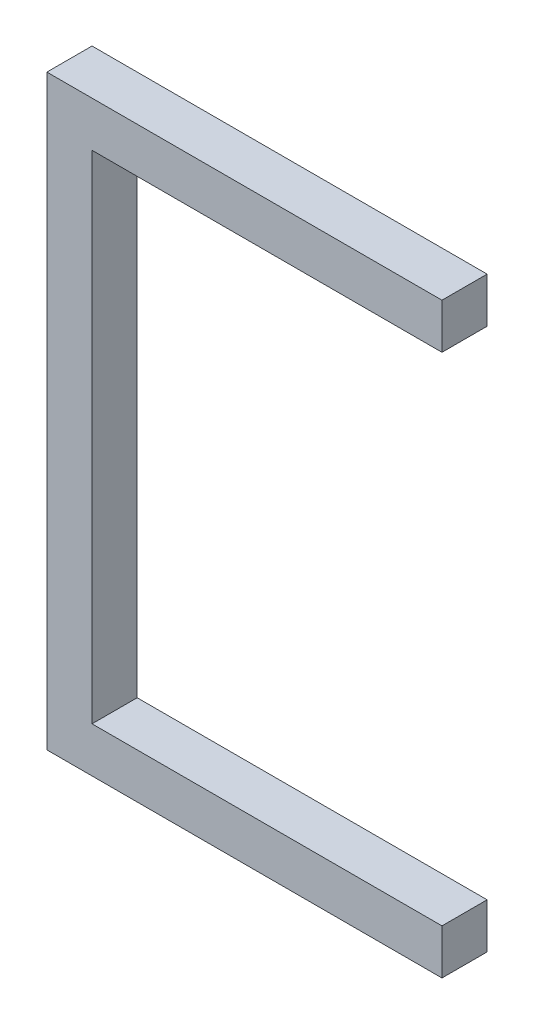
SolidWorks part; units mm, degrees
ref_plane "Front Plane" through (0, 0, 0) normal (0, 0, 1) x (1, 0, 0)
ref_plane "Top Plane" through (0, 0, 0) normal (0, 1, 0) x (1, 0, 0)
ref_plane "Right Plane" through (0, 0, 0) normal (1, 0, 0) x (0, 0, -1)
sketch "Sketch2" plane through (0, 0, 0) normal (0, 0, 1) x (1, 0, 0)
  line L14 (18.0516, 338.5499) -> (-204.1984, 338.5499)
  line L15 (-204.1984, 338.5499) -> (-204.1984, 668.7499)
  line L16 (-204.1984, 668.7499) -> (18.0516, 668.7499)
  line L17 (18.0516, 668.7499) -> (18.0516, 643.3499)
  line L18 (18.0516, 643.3499) -> (-178.7984, 643.3499)
  line L19 (-178.7984, 643.3499) -> (-178.7984, 363.9499)
  line L20 (-178.7984, 363.9499) -> (18.0516, 363.9499)
  line L21 (18.0516, 363.9499) -> (18.0516, 338.5499)
  line L22 (18.0516, 363.9499) -> (18.0516, 643.3499) construction
  dimension "D3" = 25.4
  dimension "D7" = 25.4
  dimension "D8" = 279.4
  dimension "D9" = 222.25
extrude "Boss-Extrude1" add sketch "Sketch2" along normal blind 25.4
